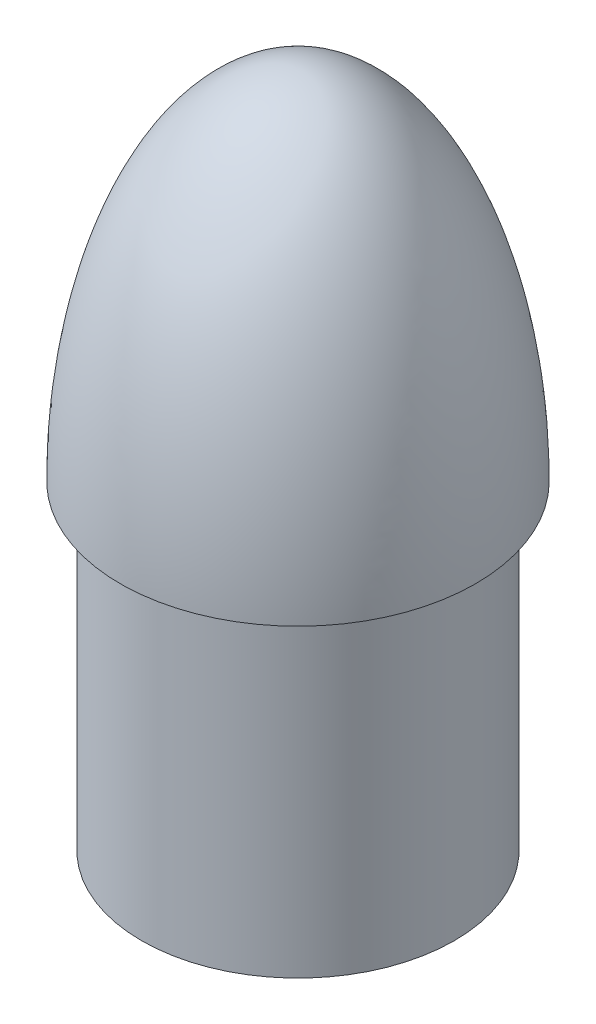
SolidWorks part; units mm, degrees
material "PA Type 6"
ref_plane "Front Plane" through (0, 0, 0) normal (0, 0, 1) x (1, 0, 0)
ref_plane "Top Plane" through (0, 0, 0) normal (0, 1, 0) x (1, 0, 0)
ref_plane "Right Plane" through (0, 0, 0) normal (1, 0, 0) x (0, 0, -1)
sketch "Sketch1" plane through (0, 0, 0) normal (0, 0, 1) x (1, 0, 0)
  line L0 (25, 0) -> (22, 0)
  line L1 (22, 0) -> (22, -45)
  line L2 (22, -45) -> (0, -45)
  line L3 (0, -45) -> (0, 50)
  line L4 (0, -27.5) -> (0, 27.5) construction
  spline S0 degree 4 poles (-2.4999, 49.7494) (-2.4224, 49.765) (-2.267, 49.795) (-2.0298, 49.8362) (-1.7223, 49.8834) (-1.3191, 49.9323) (-0.8757, 49.9753) (-0.28, 50.0026) (0.2836, 50.0026) (1.118, 49.9634) (1.8592, 49.8723) (2.6534, 49.7305) (3.4002, 49.5404) (4.0076, 49.3604) (4.5948, 49.1537) (5.1791, 48.9216) (5.8926, 48.6012) (6.8269, 48.1212) (7.9917, 47.4121) (9.344, 46.4186) (10.7229, 45.2092) (12.0365, 43.863) (13.364, 42.3032) (14.864, 40.2799) (16.4577, 37.7502) (18.0686, 34.6882) (19.5723, 31.2407) (20.8565, 27.7064) (21.943, 24.1068) (22.8484, 20.4578) (23.5857, 16.7714) (24.1646, 13.057) (24.592, 9.3253) (24.8727, 5.5923) (24.977, 2.7906) (25, 0.927) (25, 0) knots 0 0 0 0 0 0.005031 0.010061 0.015092 0.020122 0.030013 0.039903 0.049835 0.059766 0.079629 0.089561 0.099493 0.109424 0.119356 0.129288 0.139219 0.159083 0.185896 0.21569 0.245485 0.27528 0.305075 0.345513 0.405102 0.464692 0.524282 0.583872 0.643461 0.703051 0.762638 0.822224 0.881807 0.941209 1 1 1 1 1 construction
  spline S1 degree 4 poles (0, 50) (0.1503, 50) (0.4499, 49.9948) (1.118, 49.9634) (1.8592, 49.8723) (2.6534, 49.7305) (3.4002, 49.5404) (4.0076, 49.3604) (4.5948, 49.1537) (5.1791, 48.9216) (5.8926, 48.6012) (6.8269, 48.1212) (7.9917, 47.4121) (9.344, 46.4186) (10.7229, 45.2092) (12.0365, 43.863) (13.364, 42.3032) (14.864, 40.2799) (16.4577, 37.7502) (18.0686, 34.6882) (19.5723, 31.2407) (20.8565, 27.7064) (21.943, 24.1068) (22.8484, 20.4578) (23.5857, 16.7714) (24.1646, 13.057) (24.592, 9.3253) (24.8727, 5.5923) (24.977, 2.7906) (25, 0.927) (25, 0) knots 0.039903 0.039903 0.039903 0.039903 0.039903 0.049835 0.059766 0.079629 0.089561 0.099493 0.109424 0.119356 0.129288 0.139219 0.159083 0.185896 0.21569 0.245485 0.27528 0.305075 0.345513 0.405102 0.464692 0.524282 0.583872 0.643461 0.703051 0.762638 0.822224 0.881807 0.941209 1 1 1 1 1
  dimension "D1" = 45
  dimension "D2" = 22
revolve "Revolve1" add sketch "Sketch1" angle 360 about L3
